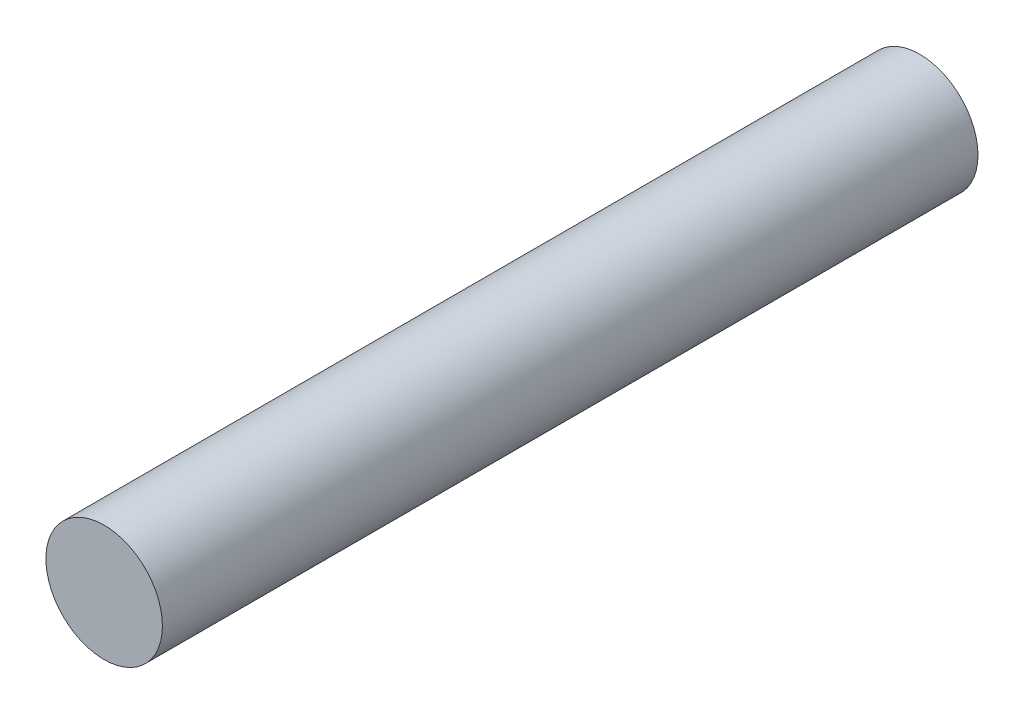
SolidWorks part; units mm, degrees
ref_plane "前视基准面" through (0, 0, 0) normal (0, 0, 1) x (1, 0, 0)
ref_plane "上视基准面" through (0, 0, 0) normal (0, 1, 0) x (1, 0, 0)
ref_plane "右视基准面" through (0, 0, 0) normal (1, 0, 0) x (0, 0, -1)
sketch "草图1" plane through (0, 0, 0) normal (0, 0, 1) x (1, 0, 0)
  circle A0 centre (0, 0) radius 2.5
  dimension "D1" = 5
extrude "凸台-拉伸1" add sketch "草图1" along normal blind 35
